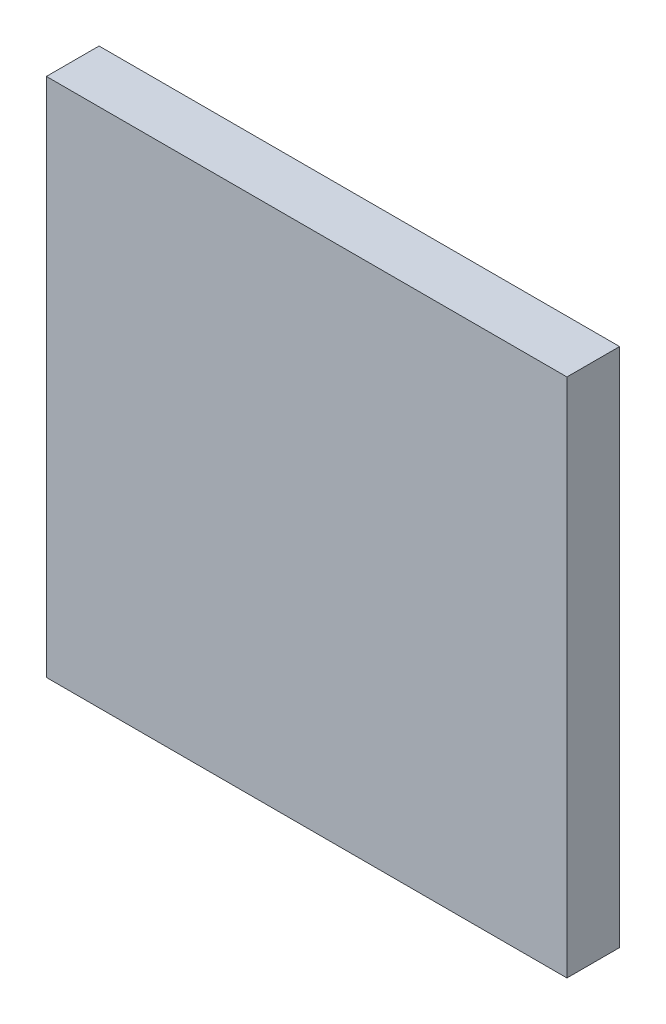
SolidWorks part; units mm, degrees
material "Polyurethane Foam Flexible"
ref_plane "Front Plane" through (0, 0, 0) normal (0, 0, 1) x (1, 0, 0)
ref_plane "Top Plane" through (0, 0, 0) normal (0, 1, 0) x (1, 0, 0)
ref_plane "Right Plane" through (0, 0, 0) normal (1, 0, 0) x (0, 0, -1)
sketch "Sketch1" plane through (0, 0, 0) normal (0, 0, 1) x (1, 0, 0)
  line L1 (-53.975, 53.975) -> (53.975, 53.975)
  line L2 (-53.975, 53.975) -> (-53.975, -53.975)
  line L3 (-53.975, -53.975) -> (53.975, -53.975)
  line L4 (53.975, 53.975) -> (53.975, -53.975)
  line L5 (-53.975, 53.975) -> (53.975, -53.975) construction
  line L6 (-53.975, -53.975) -> (53.975, 53.975) construction
  point P0 (0, 0)
  dimension "D1" = 107.95
  dimension "D2" = 107.95
extrude "Boss-Extrude1" add sketch "Sketch1" along normal mid plane 10.922
